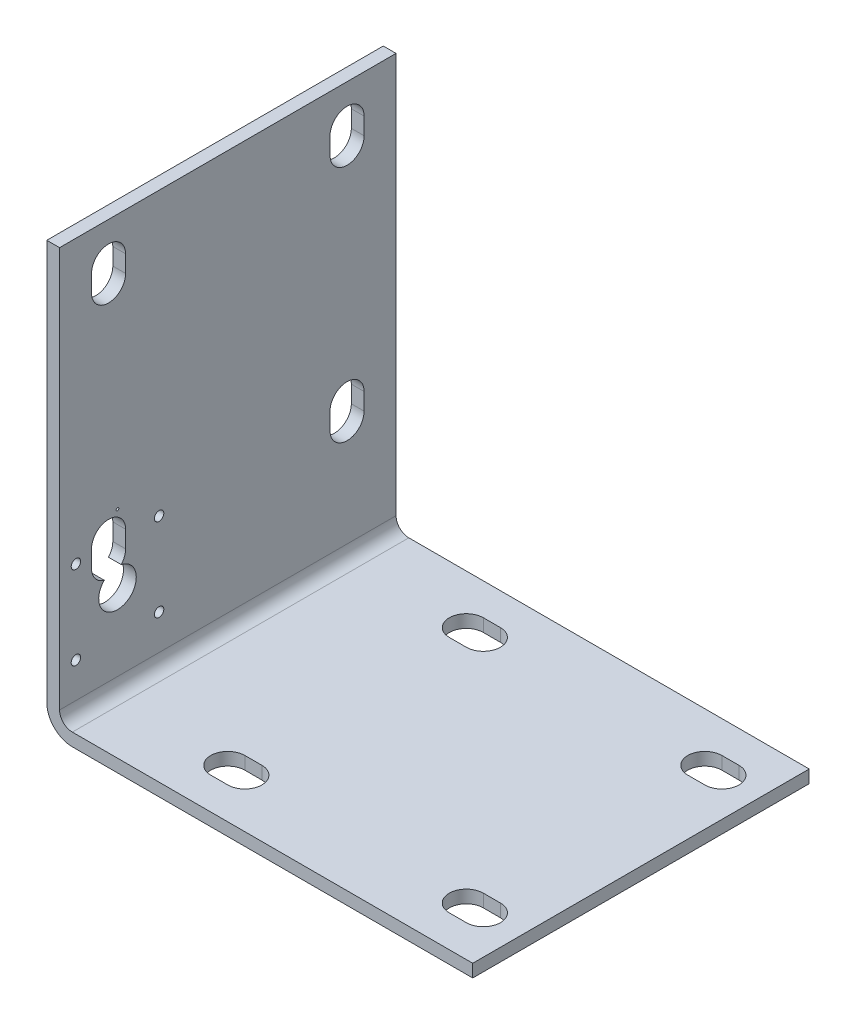
SolidWorks part; units mm, degrees
ref_plane "Front Plane" through (0, 0, 0) normal (0, 0, 1) x (1, 0, 0)
ref_plane "Top Plane" through (0, 0, 0) normal (0, 1, 0) x (1, 0, 0)
ref_plane "Right Plane" through (0, 0, 0) normal (1, 0, 0) x (0, 0, -1)
sketch "Sketch1" plane through (0, 0, 0) normal (0, 0, 1) x (1, 0, 0)
  line L0 (-9.525, 149.225) -> (-4.7625, 149.225)
  line L1 (-4.7625, 149.225) -> (-4.7625, 0)
  line L2 (0, -4.7625) -> (149.225, -4.7625)
  line L3 (149.225, -4.7625) -> (149.225, -9.525)
  line L4 (149.225, -9.525) -> (0, -9.525)
  line L5 (-9.525, 0) -> (-9.525, 149.225)
  arc A0 (-4.7625, 0) -> (0, -4.7625) centre (0, 0) ccw
  arc A1 (0, -9.525) -> (-9.525, 0) centre (0, 0) cw
  dimension "D4" = 4.7625
  dimension "D1" = 158.75
  dimension "D2" = 4.7625
  dimension "D3" = 158.75
extrude "Boss-Extrude1" add sketch "Sketch1" along normal mid plane 125.4125
ref_plane "Plane1" through (0, 0, 0) normal (0.7071, -0.7071, 0) x (-0.7071, -0.7071, 0)
sketch "Sketch2" plane through (-4.7625, 0, 0) normal (1, 0, 0) x (0, 0, -1)
  line L0 (-50.8, 134.9375) -> (-50.8, 128.5875)
  line L1 (-38.1, 128.5875) -> (-38.1, 134.9375)
  line L2 (-50.8, 46.0375) -> (-50.8, 39.6875)
  line L3 (-38.1, 39.6875) -> (-38.1, 46.0375)
  line L4 (38.1, 39.6875) -> (38.1, 46.0375)
  line L5 (50.8, 46.0375) -> (50.8, 39.6875)
  line L6 (38.1, 134.9375) -> (38.1, 128.5875)
  line L7 (50.8, 128.5875) -> (50.8, 134.9375)
  line L8 (-62.7063, 149.225) -> (62.7063, 149.225) construction
  line L9 (-44.45, 134.9375) -> (44.45, 134.9375) construction
  arc A0 (-50.8, 128.5875) -> (-38.1, 128.5875) centre (-44.45, 128.5875) ccw
  arc A1 (-38.1, 134.9375) -> (-50.8, 134.9375) centre (-44.45, 134.9375) ccw
  arc A2 (-50.8, 39.6875) -> (-38.1, 39.6875) centre (-44.45, 39.6875) ccw
  arc A3 (-38.1, 46.0375) -> (-50.8, 46.0375) centre (-44.45, 46.0375) ccw
  arc A4 (38.1, 46.0375) -> (50.8, 46.0375) centre (44.45, 46.0375) cw
  arc A5 (50.8, 39.6875) -> (38.1, 39.6875) centre (44.45, 39.6875) cw
  arc A6 (38.1, 128.5875) -> (50.8, 128.5875) centre (44.45, 128.5875) ccw
  arc A7 (50.8, 134.9375) -> (38.1, 134.9375) centre (44.45, 134.9375) ccw
  point P23 (0, 134.9375)
  point P29 (-44.45, 141.2875)
  point P30 (-44.45, 122.2375)
  point P34 (-44.45, 52.3875)
  dimension "D1" = 12.7
  dimension "D2" = 19.05
  dimension "D3" = 7.9375
  dimension "D4" = 69.85
  dimension "D5" = 76.2
extrude "Cut-Extrude1" cut sketch "Sketch2" against normal through all
mirror "Mirror1" about plane through (0, 0, 0) normal (0.7071, -0.7071, 0) of "Cut-Extrude1"
sketch "Sketch3" plane through (-4.7625, 0, 0) normal (1, 0, 0) x (0, 0, -1)
  line L1 (-56.6163, 13.075) -> (-25.6163, 13.075) construction
  line L2 (-56.6163, 13.075) -> (-56.6163, 44.075) construction
  line L3 (-56.6163, 44.075) -> (-25.6163, 44.075) construction
  line L4 (-25.6163, 13.075) -> (-25.6163, 44.075) construction
  line L5 (-56.6163, 13.075) -> (-25.6163, 44.075) construction
  line L6 (-56.6163, 44.075) -> (-25.6163, 13.075) construction
  line L7 (-62.7063, -9.525) -> (62.7063, -9.525) construction
  line L8 (-62.7063, 0) -> (-62.7063, 149.225) construction
  circle A0 centre (-41.1163, 28.575) radius 7
  circle A1 centre (-25.6163, 44.075) radius 1.75
  circle A2 centre (-56.6163, 44.075) radius 1.75
  circle A3 centre (-25.6163, 13.075) radius 1.75
  circle A4 centre (-56.6163, 13.075) radius 1.75
  circle A5 centre (-41.1163, 53.975) radius 0.5
  point P0 (-41.1163, 28.575)
  point P11 (-5.2741, 28.575)
  point P13 (0, 0)
  point P14 (40.8635, 28.575)
  dimension "D3" = 3.5
  dimension "D5" = 14
  dimension "D6" = 1
  dimension "D1" = 31
  dimension "D2" = 31
  dimension "D4" = 38.1
  dimension "D7" = 25.4
  dimension "D8" = 21.59
extrude "Cut-Extrude2" cut sketch "Sketch3" against normal through all
